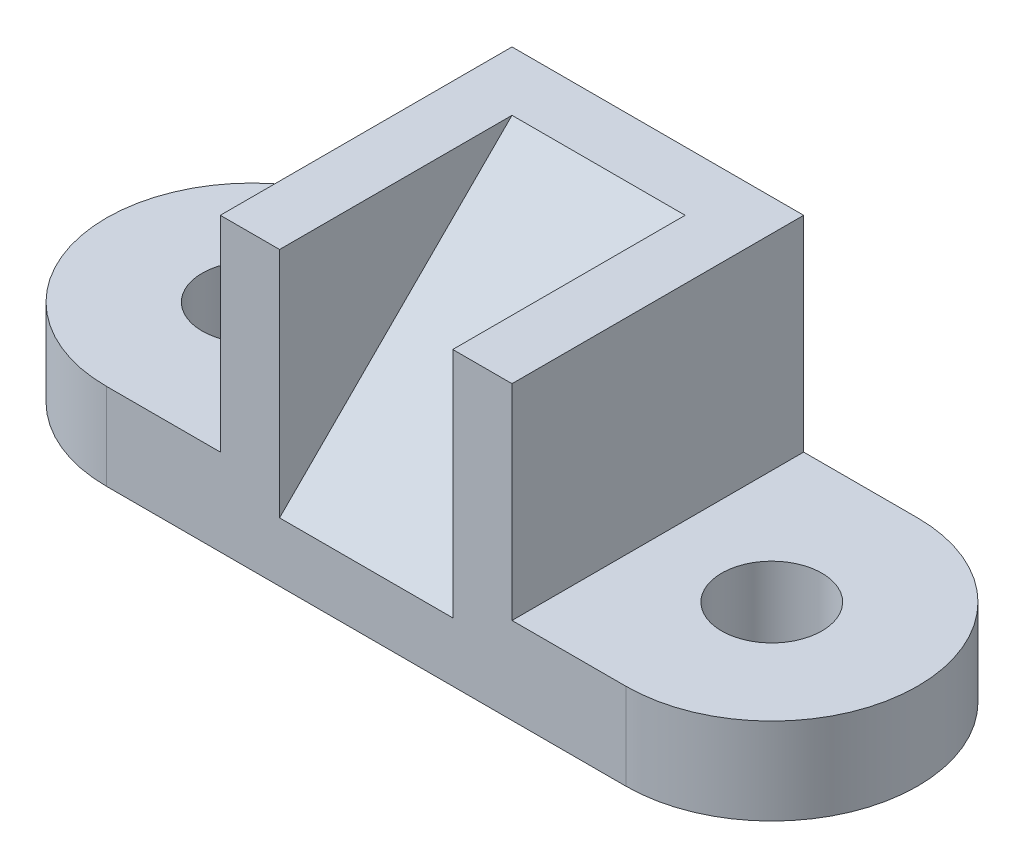
SolidWorks part; units mm, degrees
ref_plane "Front Plane" through (0, 0, 0) normal (0, 0, 1) x (1, 0, 0)
ref_plane "Top Plane" through (0, 0, 0) normal (0, 1, 0) x (1, 0, 0)
ref_plane "Right Plane" through (0, 0, 0) normal (1, 0, 0) x (0, 0, -1)
sketch "Sketch1" plane through (0, 0, 0) normal (0, 1, 0) x (1, 0, 0)
  line L0 (0, 32) -> (114, 32) construction
  line L1 (0, 0) -> (114, 0)
  line L3 (0, 64) -> (114, 64)
  line L5 (57, 64) -> (57, 0) construction
  line L6 (0, 64) -> (0, 0) construction
  line L7 (114, 64) -> (114, 0) construction
  arc A0 (0, 64) -> (0, 0) centre (0, 32) ccw
  arc A1 (114, 0) -> (114, 64) centre (114, 32) ccw
  circle A2 centre (0, 32) radius 11
  circle A3 centre (114, 32) radius 11
  dimension "D3" = 64
  dimension "D4" = 64
  dimension "D5" = 22
  dimension "D6" = 22
  dimension "D1" = 114
  dimension "D2" = 64
extrude "Boss-Extrude2" add sketch "Sketch1" along normal blind 19
sketch "Sketch2" plane through (0, 19, 0) normal (0, 1, 0) x (1, 0, 0)
  line L0 (57, 64) -> (57, 0) construction
  line L1 (114, 64) -> (0, 64) construction
  line L2 (0, 0) -> (114, 0) construction
  line L4 (89, 64) -> (25, 64)
  line L5 (89, 64) -> (89, 0)
  line L6 (89, 0) -> (25, 0)
  line L7 (25, 64) -> (25, 0)
  line L8 (89, 64) -> (25, 0) construction
  line L9 (89, 0) -> (25, 64) construction
  point P6 (57, 32)
  dimension "D1" = 64
extrude "Boss-Extrude3" add sketch "Sketch2" along normal blind 45
sketch "Sketch3" plane through (25, 0, 0) normal (-1, 0, 0) x (0, 0, 1)
  line L0 (0, 13) -> (0, 64)
  line L1 (0, 64) -> (-51, 64)
  line L2 (-64, 64) -> (0, 64) construction
  line L3 (-51, 64) -> (0, 13)
  dimension "D1" = 51
  dimension "D2" = 13
extrude "Cut-Extrude1" cut sketch "Sketch3" against normal blind 38 from offset 13
